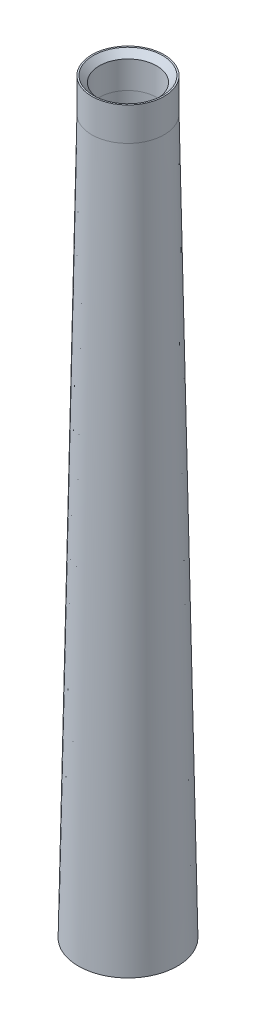
SolidWorks part; units mm, degrees
ref_plane "Front Plane" through (0, 0, 0) normal (0, 0, 1) x (1, 0, 0)
ref_plane "Top Plane" through (0, 0, 0) normal (0, 1, 0) x (1, 0, 0)
ref_plane "Right Plane" through (0, 0, 0) normal (1, 0, 0) x (0, 0, -1)
sketch "Sketch1" plane through (0, 0, 0) normal (1, 0, 0) x (0, 0, -1)
  line L0 (0, 152.4) -> (0, 0)
  line L1 (0, 0) -> (-10.5728, 0)
  line L2 (-10.5728, 0) -> (-7.7216, 152.4)
  line L3 (-7.7216, 152.4) -> (0, 152.4)
  dimension "D1" = 152.4
  dimension "D2" = 10.5728
  dimension "D3" = 7.7216
revolve "Revolve1" add sketch "Sketch1" angle 360 about L0
sketch "Sketch2" plane through (0, 0, 0) normal (1, 0, 0) x (0, 0, -1)
  line L16 (0, 152.4) -> (0, 0)
  line L17 (7.7216, 152.4) -> (-7.7216, 152.4) construction
  line L18 (-10.5728, 0) -> (10.5728, 0) construction
  line L19 (0, 0) -> (-8.985, 0)
  line L20 (-8.985, 0) -> (-6.1338, 152.4)
  line L21 (-6.1338, 152.4) -> (0, 152.4)
  line L22 (-7.7216, 152.4) -> (-10.5728, 0) construction
  line L24 (-7.7216, 152.4) -> (-10.5728, 0) construction
  line L25 (0, 287.6818) -> (0, -86.7391) construction
  dimension "D1" = 1.5875
revolve "Cut-Revolve4" cut sketch "Sketch2" angle 360 about L25
sketch "Sketch3" plane through (0, 152.4, 0) normal (0, 1, 0) x (1, 0, 0)
  circle A0 centre (0, 0) radius 6.1338
  circle A1 centre (0, 0) radius 7.7216
  circle A2 centre (0, 0) radius 6.1338 construction
  circle A3 centre (0, 0) radius 7.7216 construction
extrude "Boss-Extrude1" add sketch "Sketch3" along normal blind 7.112
chamfer "Chamfer1" distance 1.27 angle 45
